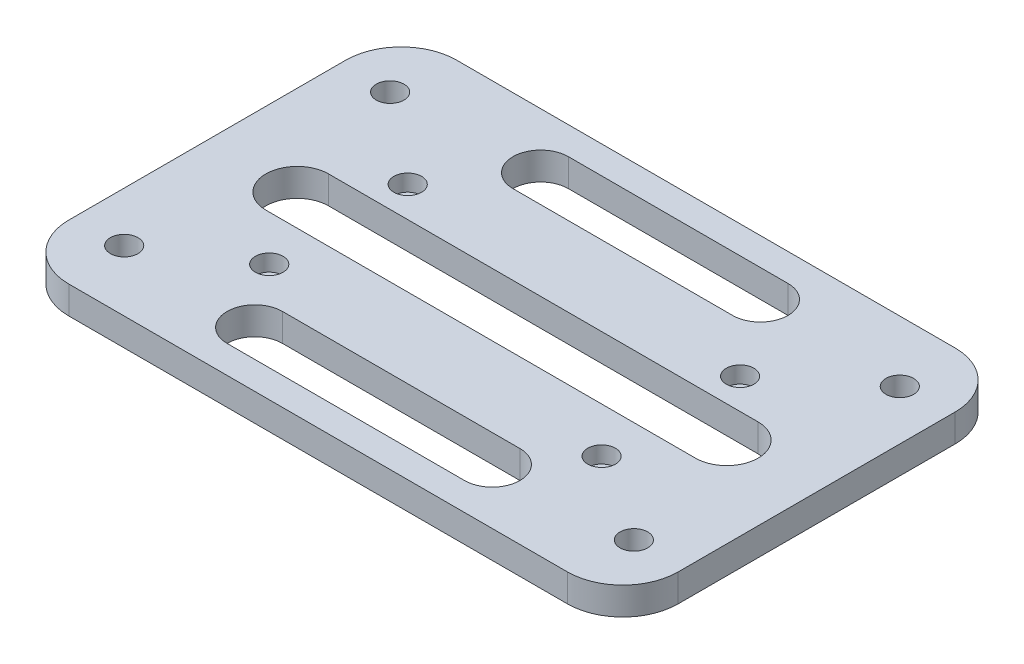
SolidWorks part; units mm, degrees
ref_plane "Plan de face" through (0, 0, 0) normal (0, 0, 1) x (1, 0, 0)
ref_plane "Plan de dessus" through (0, 0, 0) normal (0, 1, 0) x (1, 0, 0)
ref_plane "Plan de droite" through (0, 0, 0) normal (1, 0, 0) x (0, 0, -1)
sketch "Esquisse1" plane through (0, 0, 0) normal (0, 1, 0) x (1, 0, 0)
  line L1 (0, 0) -> (110, 0)
  line L2 (0, 0) -> (0, 70)
  line L3 (0, 70) -> (110, 70)
  line L4 (110, 0) -> (110, 70)
  dimension "D1" = 110
  dimension "D2" = 70
extrude "Boss.-Extru.1" add sketch "Esquisse1" along normal blind 5
sketch "Esquisse2" plane through (0, 5, 0) normal (0, 1, 0) x (1, 0, 0)
  line L1 (9, 59) -> (9, 11) construction
  line L2 (9, 11) -> (101, 11) construction
  line L3 (0, 70) -> (0, 0) construction
  line L4 (0, 0) -> (110, 0) construction
  line L5 (25, 46.1768) -> (25, 68.6768) construction
  line L6 (25, 21.1768) -> (25, 8.6768) construction
  line L7 (110, 0) -> (110, 70) construction
  circle A0 centre (9, 59) radius 2.5
  circle A1 centre (9, 11) radius 2.5
  circle A2 centre (101, 11) radius 2.5
  circle A3 centre (101, 59) radius 2.5
  circle A4 centre (25, 46.1768) radius 1.3
  circle A5 centre (25, 21.1768) radius 1.3
  circle A6 centre (85, 21.1768) radius 1.3
  circle A7 centre (85, 46.1768) radius 1.3
  point P8 (9, 35)
  point P11 (0, 35)
  point P12 (55, 11)
  point P15 (55, 0)
  dimension "D5" = 5
  dimension "D6" = 2.6
  dimension "D1" = 48
  dimension "D2" = 48
  dimension "D3" = 92
  dimension "D4" = 92
  dimension "D7" = 25
  dimension "D8" = 22.5
  dimension "D9" = 12.5
  dimension "D10" = 25
  dimension "D11" = 25
extrude "Enlèv. mat.-Extru.1" cut sketch "Esquisse2" against normal through all
sketch "Esquisse4" plane through (0, 5, 0) normal (0, 1, 0) x (1, 0, 0)
  circle A0 centre (25, 46.1768) radius 2.5
  circle A1 centre (25, 21.1768) radius 2.5
  circle A2 centre (85, 21.1768) radius 2.5
  circle A3 centre (85, 46.1768) radius 2.5
  dimension "D1" = 5
extrude "Enlèv. mat.-Extru.2" cut sketch "Esquisse4" against normal blind 3
sketch "Esquisse5" plane through (0, 5, 0) normal (0, 1, 0) x (1, 0, 0)
  line L0 (35.1751, 60) -> (74.8249, 60) construction
  line L1 (35.1751, 65) -> (74.8249, 65)
  line L2 (35.1751, 55) -> (74.8249, 55)
  line L3 (16.2261, 35) -> (93.7739, 35) construction
  line L4 (16.2261, 40.6597) -> (93.7739, 40.6597)
  line L5 (16.2261, 29.3403) -> (93.7739, 29.3403)
  line L6 (33.5667, 10) -> (76.4333, 10) construction
  line L7 (33.5667, 15) -> (76.4333, 15)
  line L8 (33.5667, 5) -> (76.4333, 5)
  line L9 (110, 70) -> (0, 70) construction
  line L10 (0, 70) -> (0, 0) construction
  line L11 (0, 0) -> (110, 0) construction
  arc A0 (35.1751, 65) -> (35.1751, 55) centre (35.1751, 60) ccw
  arc A1 (74.8249, 55) -> (74.8249, 65) centre (74.8249, 60) ccw
  arc A2 (16.2261, 40.6597) -> (16.2261, 29.3403) centre (16.2261, 35) ccw
  arc A3 (93.7739, 29.3403) -> (93.7739, 40.6597) centre (93.7739, 35) ccw
  arc A4 (33.5667, 15) -> (33.5667, 5) centre (33.5667, 10) ccw
  arc A5 (76.4333, 5) -> (76.4333, 15) centre (76.4333, 10) ccw
  point P2 (55, 60)
  point P9 (55, 35)
  point P16 (55, 10)
  point P21 (0, 0)
  point P24 (55, 70)
  point P25 (0, 0)
  point P28 (0, 35)
  point P29 (16.2261, 35)
  dimension "D2" = 5
  dimension "D1" = 5
  dimension "D3" = 5
  dimension "D4" = 5
extrude "Enlèv. mat.-Extru.3" cut sketch "Esquisse5" against normal through all
fillet "Congé1" radius 10 4 edges at (110, 2.5, -70) (110, 2.5, 0) (0, 2.5, 0) (0, 2.5, -70)
